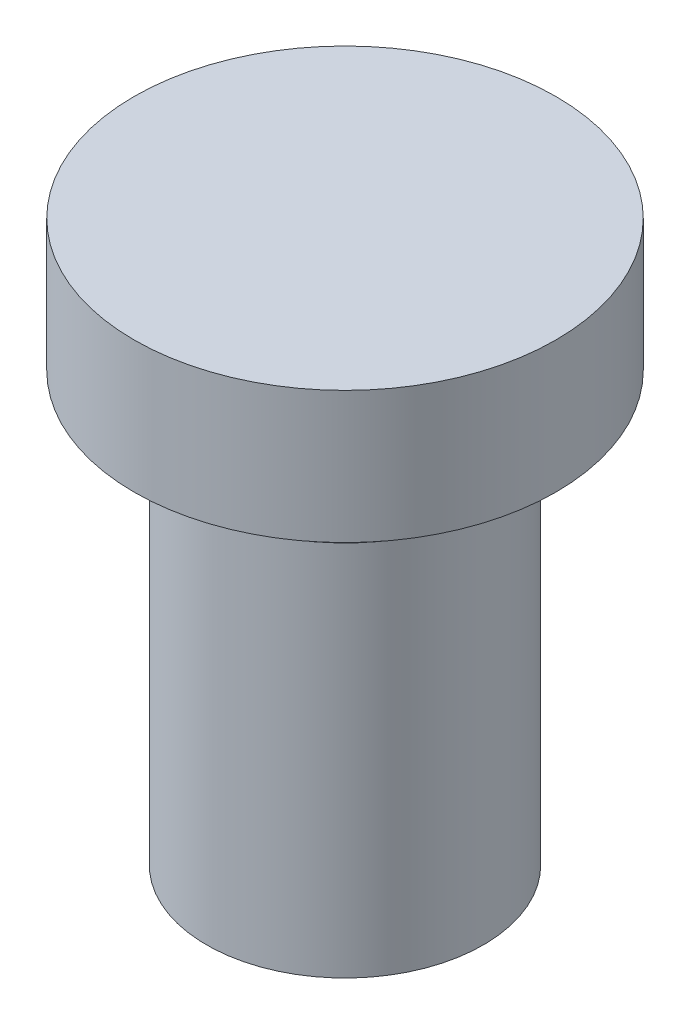
SolidWorks part; units mm, degrees
ref_plane "Front Plane" through (0, 0, 0) normal (0, 0, 1) x (1, 0, 0)
ref_plane "Top Plane" through (0, 0, 0) normal (0, 1, 0) x (1, 0, 0)
ref_plane "Right Plane" through (0, 0, 0) normal (1, 0, 0) x (0, 0, -1)
sketch "Sketch1" plane through (0, 0, 0) normal (0, 0, 1) x (1, 0, 0)
  line L0 (0, 0) -> (0, 4.25)
  line L1 (0, 4.25) -> (1.6, 4.25)
  line L2 (1.6, 4.25) -> (1.6, 3.25)
  line L4 (1.05, 3) -> (1.05, 0)
  line L5 (1.05, 0) -> (0, 0)
  line L7 (1.05, 3) -> (1.25, 3)
  line L8 (1.25, 3) -> (1.25, 3.25)
  line L9 (1.25, 3.25) -> (1.6, 3.25)
  dimension "D1" = 1.05
  dimension "D3" = 0.25
  dimension "D2" = 1.6
  dimension "D4" = 1
  dimension "D5" = 0.2
  dimension "D6" = 3
revolve "Revolve1" add sketch "Sketch1" angle 360 about L0
